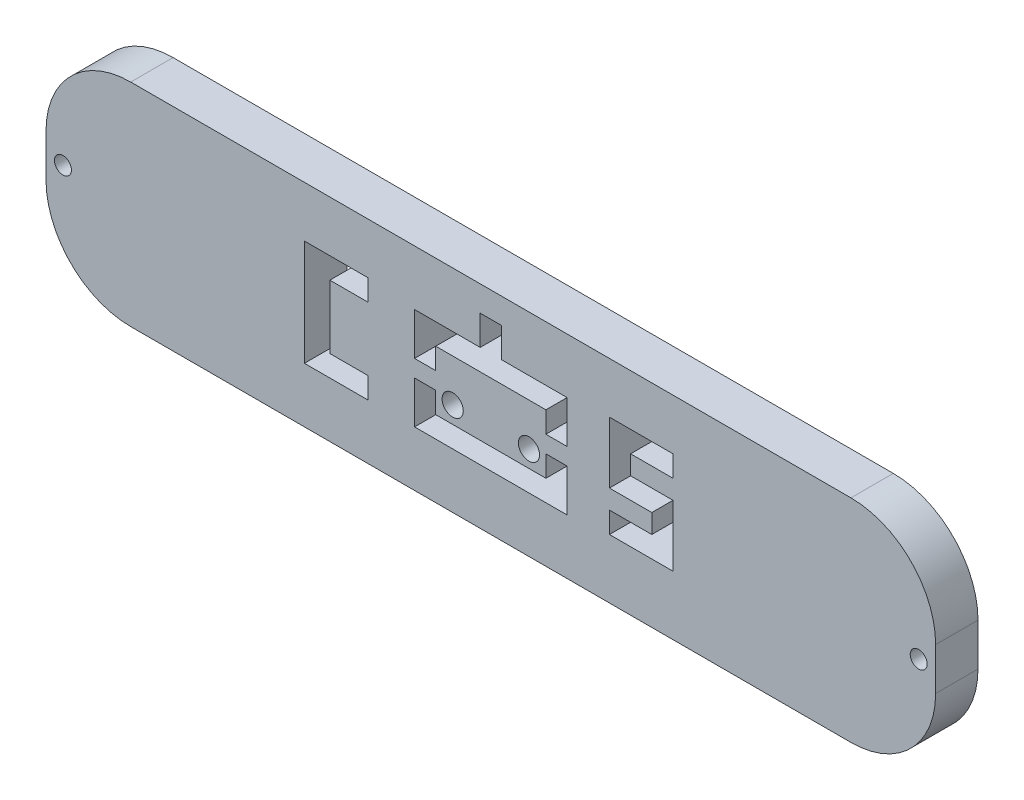
SolidWorks part; units mm, degrees
ref_plane "Alzado" through (0, 0, 0) normal (0, 0, 1) x (1, 0, 0)
ref_plane "Planta" through (0, 0, 0) normal (0, 1, 0) x (1, 0, 0)
ref_plane "Vista lateral" through (0, 0, 0) normal (1, 0, 0) x (0, 0, -1)
sketch "Croquis1" plane through (0, 0, 0) normal (0, 0, 1) x (1, 0, 0)
  line L0 (105, -50) -> (105, 0) construction
  line L1 (0, 0) -> (210, 0)
  line L2 (0, 0) -> (0, -50)
  line L3 (0, -50) -> (210, -50)
  line L4 (210, 0) -> (210, -50)
  line L5 (97.2718, -25) -> (112.9329, -25) construction
  line L6 (87, -13) -> (92, -13)
  line L7 (87, -13) -> (87, -23)
  line L8 (87, -23) -> (92, -23)
  line L9 (92, -13) -> (92, -23)
  line L10 (87, -13) -> (123, -13)
  line L11 (87, -13) -> (87, -18)
  line L12 (87, -18) -> (123, -18)
  line L13 (123, -13) -> (123, -18)
  line L14 (123, -13) -> (118, -13)
  line L15 (123, -13) -> (123, -23)
  line L16 (123, -23) -> (118, -23)
  line L17 (118, -13) -> (118, -23)
  line L18 (123, -27) -> (118, -27)
  line L19 (123, -37) -> (123, -27)
  line L20 (118, -37) -> (118, -27)
  line L21 (87, -37) -> (123, -37)
  line L22 (87, -32) -> (123, -32)
  line L23 (87, -37) -> (87, -27)
  line L24 (87, -27) -> (92, -27)
  line L25 (92, -37) -> (92, -27)
  line L27 (102.5, -6) -> (107.5, -6)
  line L28 (102.5, -6) -> (102.5, -18)
  line L29 (102.5, -18) -> (107.5, -18)
  line L30 (107.5, -6) -> (107.5, -18)
  line L31 (76, -12) -> (61, -12)
  line L32 (76, -12) -> (76, -17)
  line L33 (76, -17) -> (61, -17)
  line L34 (61, -12) -> (61, -17)
  line L35 (61, -12) -> (67, -12)
  line L36 (61, -12) -> (61, -37)
  line L37 (61, -37) -> (67, -37)
  line L38 (67, -12) -> (67, -37)
  line L39 (61, -37) -> (76, -37)
  line L40 (61, -37) -> (61, -32)
  line L41 (61, -32) -> (76, -32)
  line L42 (76, -37) -> (76, -32)
  line L43 (148, -12) -> (133, -12)
  line L44 (148, -12) -> (148, -17)
  line L45 (148, -17) -> (133, -17)
  line L46 (133, -12) -> (133, -17)
  line L47 (133, -12) -> (138, -12)
  line L48 (133, -12) -> (133, -26.5)
  line L49 (133, -26.5) -> (138, -26.5)
  line L50 (138, -12) -> (138, -26.5)
  line L51 (133, -26.5) -> (148, -26.5)
  line L52 (133, -26.5) -> (133, -21.5)
  line L53 (133, -21.5) -> (148, -21.5)
  line L54 (148, -26.5) -> (148, -21.5)
  line L55 (148, -21.5) -> (143, -21.5)
  line L56 (148, -21.5) -> (148, -31)
  line L57 (148, -31) -> (143, -31)
  line L58 (143, -21.5) -> (143, -31)
  line L59 (148, -31) -> (133, -31)
  line L60 (148, -31) -> (148, -36)
  line L61 (148, -36) -> (133, -36)
  line L62 (133, -31) -> (133, -36)
  circle A0 centre (4, -25) radius 2
  circle A1 centre (206, -25) radius 2
  circle A2 centre (96, -28) radius 2.5
  circle A3 centre (114, -28) radius 2.5
  dimension "D3" = 4
  dimension "D4" = 101
  dimension "D5" = 25
  dimension "D6" = 4
  dimension "D7" = 25
  dimension "D8" = 101
  dimension "D17" = 5
  dimension "D18" = 4
  dimension "D19" = 4
  dimension "D20" = 5
  dimension "D21" = 4
  dimension "D22" = 4
  dimension "D45" = 25
  dimension "D30" = 20
  dimension "D31" = 15
  dimension "D32" = 15
  dimension "D33" = 5
  dimension "D34" = 15
  dimension "D35" = 5
  dimension "D1" = 210
  dimension "D2" = 50
  dimension "D9" = 13
  dimension "D10" = 5
  dimension "D11" = 10
  dimension "D12" = 13
  dimension "D13" = 5
  dimension "D14" = 5
  dimension "D15" = 13
  dimension "D16" = 10
  dimension "D23" = 2.5
  dimension "D24" = 2.5
  dimension "D25" = 12
  dimension "D26" = 5
  dimension "D27" = 5
  dimension "D28" = 6
  dimension "D29" = 12
  dimension "D36" = 5
  dimension "D37" = 5
  dimension "D38" = 5
  dimension "D39" = 4.5
  dimension "D40" = 4.5
  dimension "D41" = 20
  dimension "D42" = 25
  dimension "D43" = 15
extrude "Saliente-Extruir1" add sketch "Croquis1" along normal blind 10 contours L1 L30 L10 L13 L15 L16 L17 L12 L9 L8 L7 L6 L28 L2 L3 L4 A3 A2 A1 A0 L25 L22 L20 L18 L19 L21 L23 L24
fillet "Redondeo1" radius 20 4 edges at (210, 0, 5) (210, -50, 5) (0, -50, 5) (0, 0, 5)
